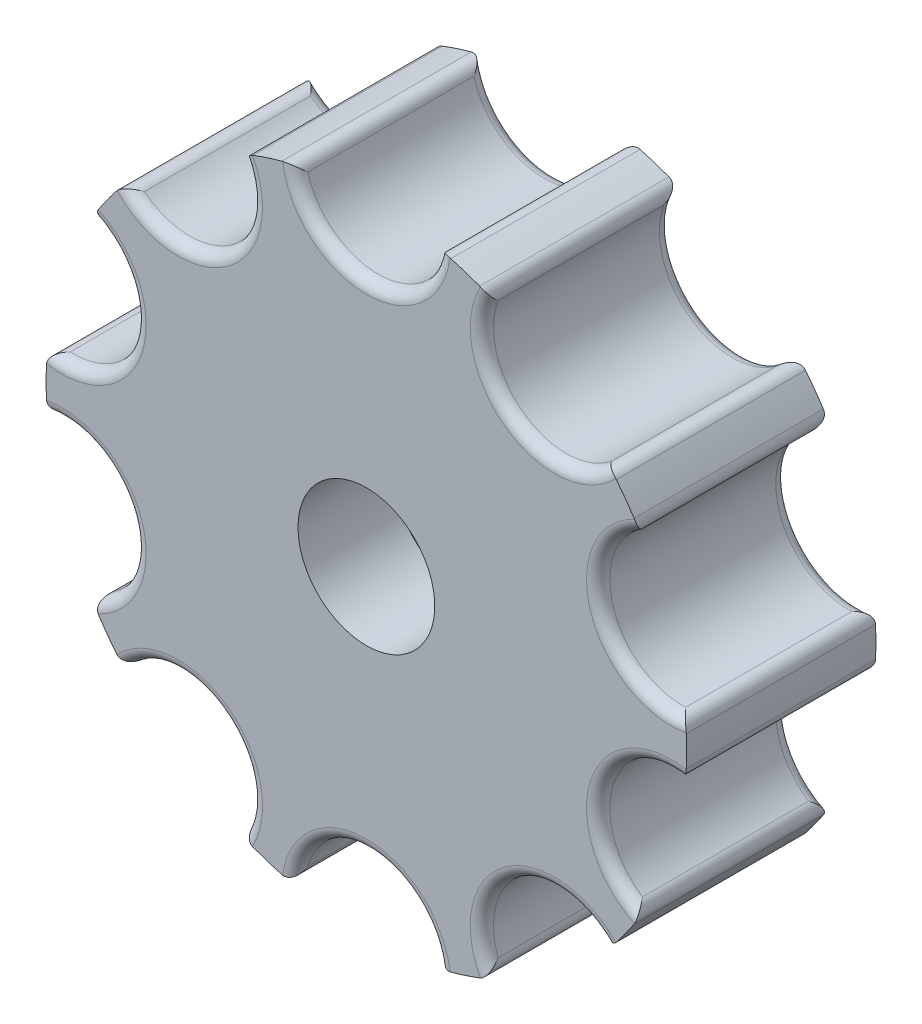
SolidWorks part; units mm, degrees
ref_plane "Front Plane" through (0, 0, 0) normal (0, 0, 1) x (1, 0, 0)
ref_plane "Top Plane" through (0, 0, 0) normal (0, 1, 0) x (1, 0, 0)
ref_plane "Right Plane" through (0, 0, 0) normal (1, 0, 0) x (0, 0, -1)
sketch "Sketch1" plane through (0, 0, 0) normal (0, 0, 1) x (1, 0, 0)
  circle A0 centre (0, 0) radius 11
  circle A1 centre (0, 0) radius 2.35
  dimension "D1" = 22
extrude "Boss-Extrude1" add sketch "Sketch1" along normal blind 6.5
sketch "Sketch2" plane through (0, 0, 6.5) normal (0, 0, 1) x (1, 0, 0)
  circle A0 centre (0, -11) radius 2.5
  circle A1 centre (0, 0) radius 11 construction
  circle A2 centre (-6.4656, -8.8992) radius 2.5
  circle A3 centre (-10.4616, -3.3992) radius 2.5
  circle A4 centre (-10.4616, 3.3992) radius 2.5
  circle A5 centre (-6.4656, 8.8992) radius 2.5
  circle A6 centre (0, 11) radius 2.5
  circle A7 centre (6.4656, 8.8992) radius 2.5
  circle A8 centre (10.4616, 3.3992) radius 2.5
  circle A9 centre (10.4616, -3.3992) radius 2.5
  circle A10 centre (6.4656, -8.8992) radius 2.5
  point P22 (0, 0)
  dimension "D1" = 5
  dimension "D2" = 10
extrude "Cut-Extrude1" cut sketch "Sketch2" against normal blind 7.5
fillet "Fillet1" radius 0.4 40 edges at (-10.959, 0.9492, 3.25) (-9.4239, 5.6736, 3.25) (-8.084, 2.6266, 6.5) (-8.084, 2.6266, 0) (-8.3081, 7.2094, 3.25) (-4.2892, 10.1293, 3.25) (-4.9962, 6.8766, 6.5) (-4.9962, 6.8766, 0) (-2.4838, 10.7159, 3.25) (2.4838, 10.7159, 3.25) (0, 8.5, 6.5) (0, 8.5, 0) (9.4239, 5.6736, 3.25) (10.959, 0.9492, 3.25) (8.084, 2.6266, 6.5) (8.084, 2.6266, 0) (10.959, -0.9492, 3.25) (9.4239, -5.6736, 3.25) (8.084, -2.6266, 6.5) (8.084, -2.6266, 0) (8.3081, -7.2094, 3.25) (4.2892, -10.1293, 3.25) (4.9962, -6.8766, 6.5) (4.9962, -6.8766, 0) (4.2892, 10.1293, 3.25) (8.3081, 7.2094, 3.25) (4.9962, 6.8766, 6.5) (4.9962, 6.8766, 0) (2.4838, -10.7159, 3.25) (-2.4838, -10.7159, 3.25) (0, -8.5, 6.5) (0, -8.5, 0) (-4.2892, -10.1293, 3.25) (-8.3081, -7.2094, 3.25) (-4.9962, -6.8766, 6.5) (-4.9962, -6.8766, 0) (-9.4239, -5.6736, 3.25) (-10.959, -0.9492, 3.25) (-8.084, -2.6266, 6.5) (-8.084, -2.6266, 0)
sketch "Sketch3" plane through (0, 0, 0) normal (0, 0, -1) x (-1, 0, 0)
  line L1 (4.3301, 0) -> (2.1651, 3.75)
  line L2 (2.1651, 3.75) -> (-2.1651, 3.75)
  line L3 (-2.1651, 3.75) -> (-4.3301, 0)
  line L4 (-4.3301, 0) -> (-2.1651, -3.75)
  line L5 (-2.1651, -3.75) -> (2.1651, -3.75)
  line L6 (2.1651, -3.75) -> (4.3301, 0)
  circle A0 centre (0, 0) radius 3.75 construction
  dimension "D1" = 7.5
extrude "Cut-Extrude2" cut sketch "Sketch3" against normal blind 3.2
